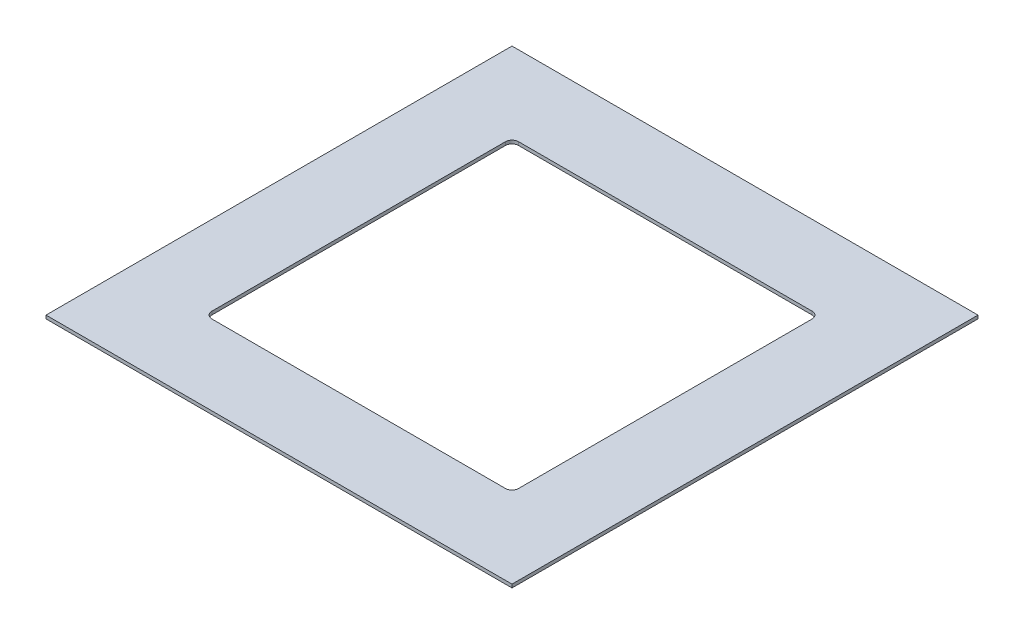
SolidWorks part; units mm, degrees
material "Rubber"
ref_plane "Front Plane" through (0, 0, 0) normal (0, 0, 1) x (1, 0, 0)
ref_plane "Top Plane" through (0, 0, 0) normal (0, 1, 0) x (1, 0, 0)
ref_plane "Right Plane" through (0, 0, 0) normal (1, 0, 0) x (0, 0, -1)
sketch "Sketch1" plane through (0, 0, 0) normal (0, 1, 0) x (1, 0, 0)
  line L1 (-69.85, -69.85) -> (69.85, -69.85)
  line L2 (-69.85, -69.85) -> (-69.85, 69.85)
  line L3 (-69.85, 69.85) -> (69.85, 69.85)
  line L4 (69.85, -69.85) -> (69.85, 69.85)
  line L5 (-69.85, -69.85) -> (69.85, 69.85) construction
  line L6 (-69.85, 69.85) -> (69.85, -69.85) construction
  line L7 (-46, -46) -> (46, -46)
  line L8 (-46, -46) -> (-46, 46)
  line L9 (-46, 46) -> (46, 46)
  line L10 (46, -46) -> (46, 46)
  line L11 (-46, -46) -> (46, 46) construction
  line L12 (-46, 46) -> (46, -46) construction
  point P0 (0, 0)
  point P6 (0, 0)
  dimension "D1" = 139.7
  dimension "D2" = 92
extrude "Boss-Extrude1" add sketch "Sketch1" along normal mid plane 1
fillet "Fillet1" radius 2 4 edges at (-46, 0, 46) (46, 0, 46) (46, 0, -46) (-46, 0, -46)
